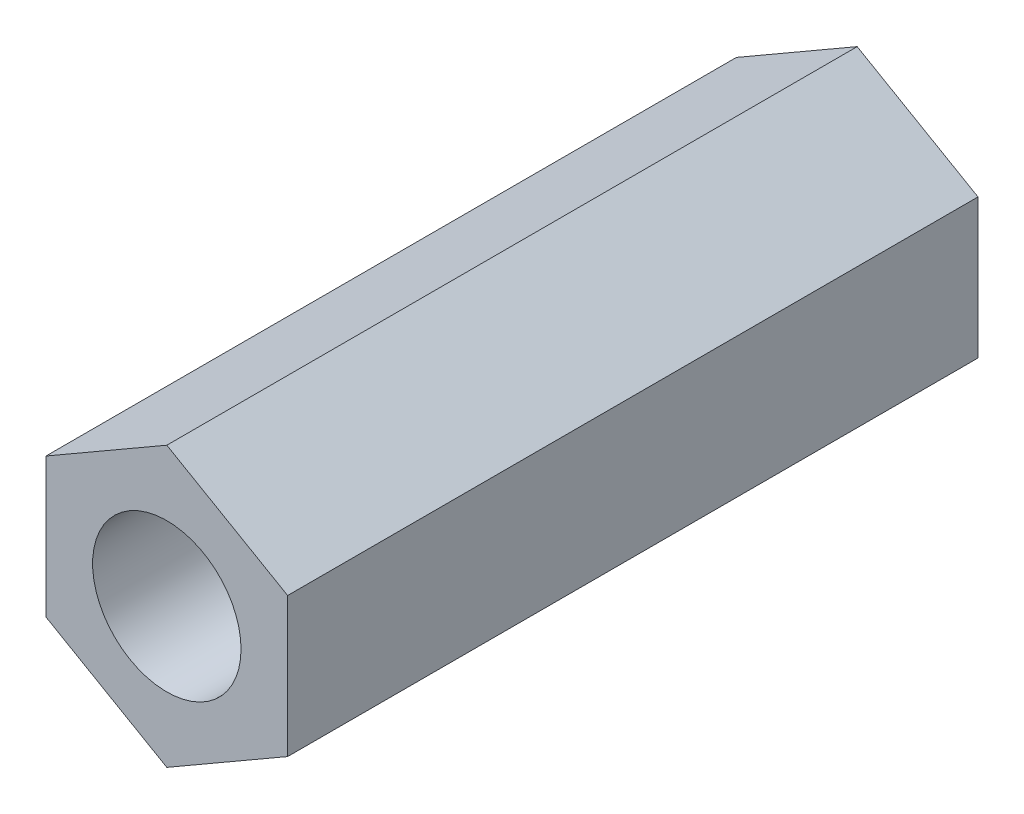
SolidWorks part; units mm, degrees
ref_plane "前视基准面" through (0, 0, 0) normal (0, 0, 1) x (1, 0, 0)
ref_plane "上视基准面" through (0, 0, 0) normal (0, 1, 0) x (1, 0, 0)
ref_plane "右视基准面" through (0, 0, 0) normal (1, 0, 0) x (0, 0, -1)
sketch "草图1" plane through (0, 0, 0) normal (0, 0, 1) x (1, 0, 0)
  line L1 (3.5, -2.0207) -> (3.5, 2.0207)
  line L2 (3.5, 2.0207) -> (0, 4.0415)
  line L3 (0, 4.0415) -> (-3.5, 2.0207)
  line L4 (-3.5, 2.0207) -> (-3.5, -2.0207)
  line L5 (-3.5, -2.0207) -> (0, -4.0415)
  line L6 (0, -4.0415) -> (3.5, -2.0207)
  circle A0 centre (0, 0) radius 3.5 construction
  circle A1 centre (0, 0) radius 2.15
  dimension "D2" = 4.3
  dimension "D1" = 7
extrude "凸台-拉伸1" add sketch "草图1" along normal blind 20
